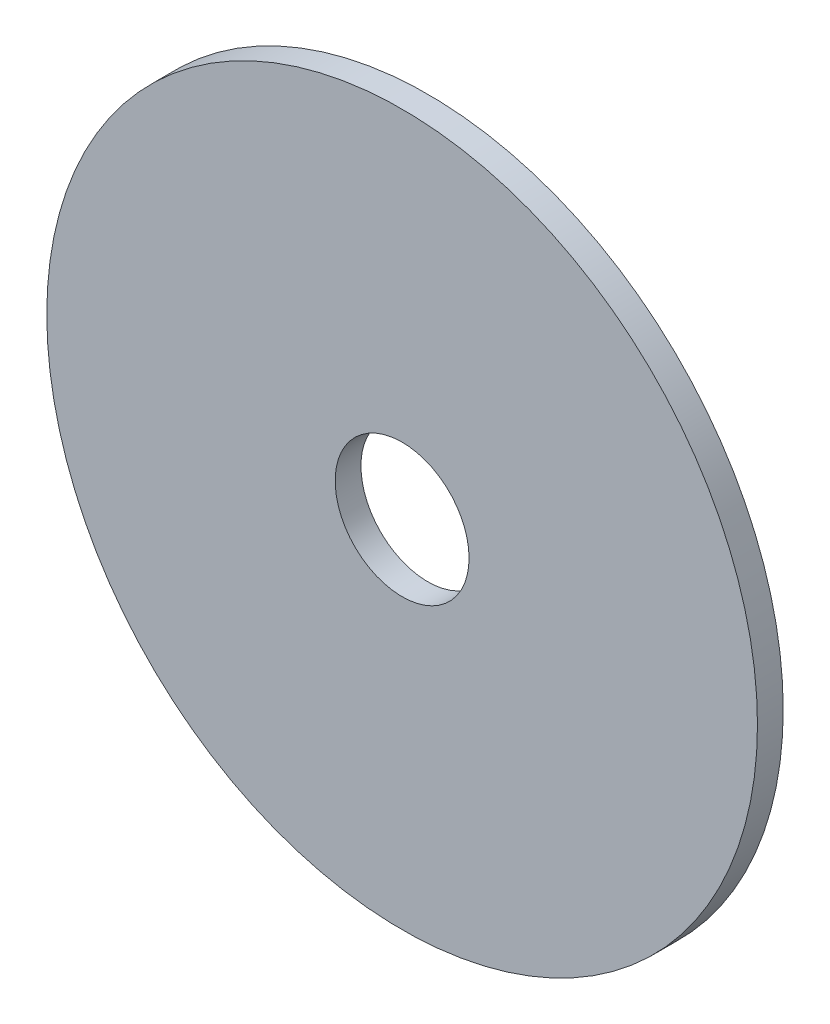
SolidWorks part; units mm, degrees
ref_plane "Front" through (0, 0, 0) normal (0, 0, 1) x (1, 0, 0)
ref_plane "Top" through (0, 0, 0) normal (0, 1, 0) x (1, 0, 0)
ref_plane "Right" through (0, 0, 0) normal (1, 0, 0) x (0, 0, -1)
sketch "Sketch1" plane through (0, 0, 0) normal (0, 0, 1) x (1, 0, 0)
  circle A0 centre (0, 0) radius 17.526
  circle A1 centre (0, 0) radius 3.302
  dimension "OD" = 35.052
  dimension "ID" = 6.604
extrude "Boss-Extrude1" add sketch "Sketch1" along normal mid plane 1.27
